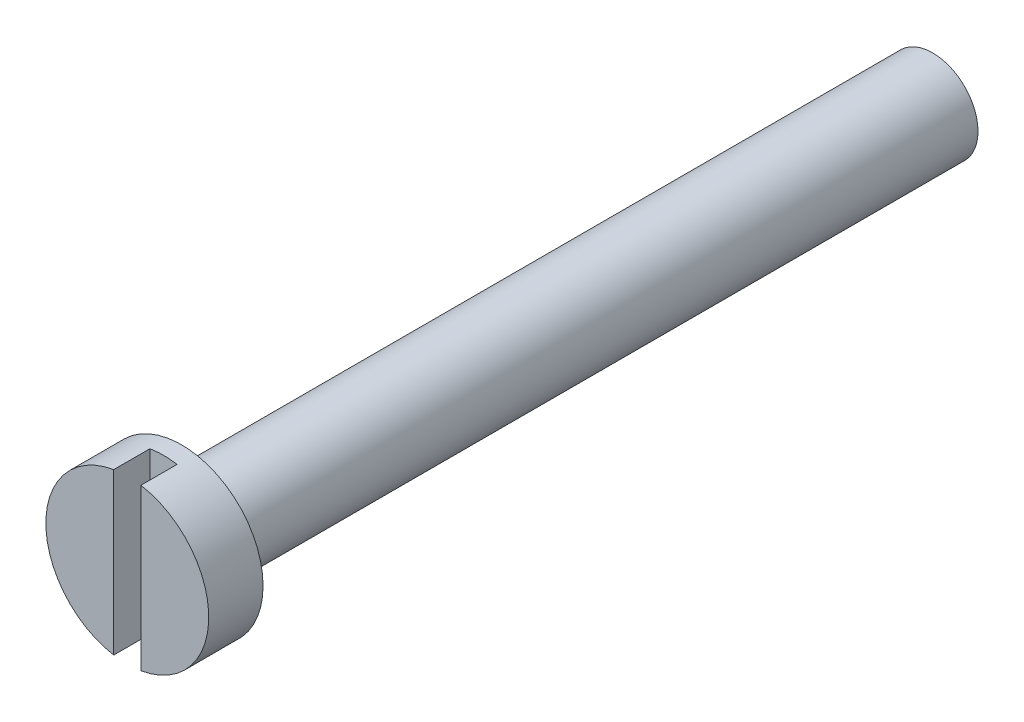
SolidWorks part; units mm, degrees
ref_plane "前视基准面" through (0, 0, 0) normal (0, 0, 1) x (1, 0, 0)
ref_plane "上视基准面" through (0, 0, 0) normal (0, 1, 0) x (1, 0, 0)
ref_plane "右视基准面" through (0, 0, 0) normal (1, 0, 0) x (0, 0, -1)
sketch "草图1" plane through (0, 0, 0) normal (0, 0, 1) x (1, 0, 0)
  circle A0 centre (0, 0) radius 2.5
  dimension "D1" = 5
extrude "凸台-拉伸1" add sketch "草图1" along normal blind 41.5
cosmetic thread "装饰螺纹线2" parameters "D1"=10, "D2"=4.134
sketch "草图2" plane through (0, 0, 41.5) normal (0, 0, 1) x (1, 0, 0)
  circle A0 centre (0, 0) radius 4.5
  dimension "D1" = 9
extrude "凸台-拉伸2" add sketch "草图2" along normal blind 3
sketch "草图4" plane through (0, 0, 44.5) normal (0, 0, 1) x (1, 0, 0)
  line L1 (-0.75, 5.4684) -> (0.75, 5.4684)
  line L2 (-0.75, 5.4684) -> (-0.75, -5.4684)
  line L3 (-0.75, -5.4684) -> (0.75, -5.4684)
  line L4 (0.75, 5.4684) -> (0.75, -5.4684)
  line L5 (-0.75, 5.4684) -> (0.75, -5.4684) construction
  line L6 (-0.75, -5.4684) -> (0.75, 5.4684) construction
  point P0 (0, 0)
  dimension "D1" = 1.5
extrude "切除-拉伸1" cut sketch "草图4" against normal blind 2
sketch "草图5" plane through (0, 0, 0) normal (0, 0, -1) x (-1, 0, 0)
  point P0 (0, 0)
  point P1 (-8.9921, 4.042)
hole_wizard "M3 螺纹孔的螺纹孔钻头1" positions "草图6" profile "草图8" hole size "M3" standard "GB"
sketch "草图6" plane through (0, 0, 0) normal (0, 0, -1) x (-1, 0, 0)
  point P0 (0, 0)
sketch "草图8" plane through (0, 0, 0) normal (1, 0, 0) x (0, 1, 0)
  line L0 (0, 0) -> (0, 10.7511)
  line L1 (0, 10.7511) -> (1.25, 10)
  line L2 (1.25, 10) -> (1.25, 0)
  line L5 (1.25, 0) -> (0, 0)
  line L10 (0, 10.7511) -> (-1.25, 10) construction
  line L11 (0, -6.35) -> (0, 107.95) construction
  dimension "孔直径" = 2.5
  dimension "孔深度" = 10
  dimension "导头角度" = 118
